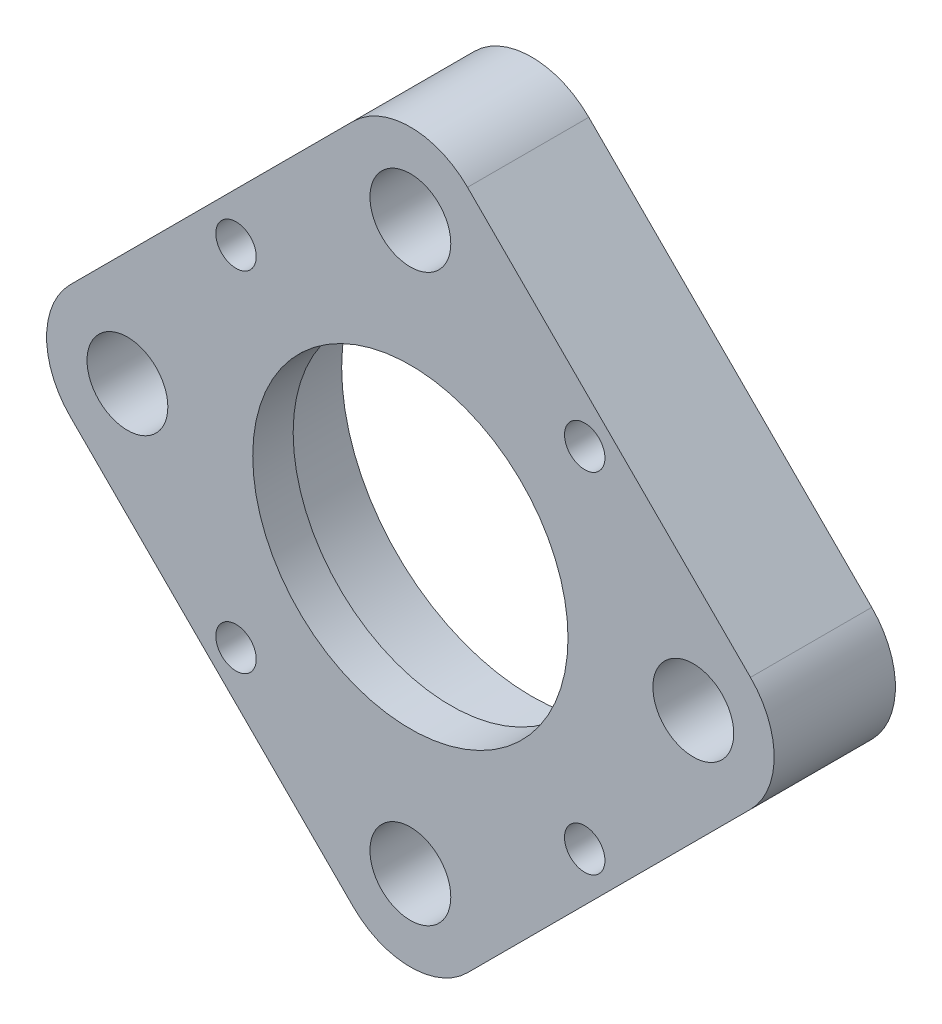
SolidWorks part; units mm, degrees
material "Stop 1060"
ref_plane "Płaszczyzna przednia" through (0, 0, 0) normal (0, 0, 1) x (1, 0, 0)
ref_plane "Płaszczyzna górna" through (0, 0, 0) normal (0, 1, 0) x (1, 0, 0)
ref_plane "Płaszczyzna prawa" through (0, 0, 0) normal (1, 0, 0) x (0, 0, -1)
sketch "Szkic1" plane through (0, 0, 0) normal (0, 0, 1) x (1, 0, 0)
  circle A0 centre (0, 0) radius 23.5
  circle A1 centre (0, 0) radius 19.5
  circle A2 centre (0, 0) radius 35
  dimension "D1" = 39
  dimension "D2" = 47
extrude "Dodanie-wyciągnięcie3" add sketch "Szkic1" along normal blind 5 contours A2 A0 | A0 A1
sketch "Szkic4" plane through (0, 0, 0) normal (0, 0, -1) x (-1, 0, 0)
  circle A0 centre (0, 0) radius 23.5
  circle A1 centre (0, 0) radius 35
  circle M2 centre (0, 0) radius 35
  dimension "D1" = 47
extrude "Dodanie-wyciągnięcie5" add sketch "Szkic4" along normal blind 10 contours A0 M2 | A1
sketch "Szkic10" plane through (0, 0, -10) normal (0, 0, -1) x (-1, 0, 0)
  circle A0 centre (0, 0) radius 30.5
  point P5 (-30.5, 0)
  point P6 (30.5, 0)
sketch "Szkic13" plane through (0, 0, -10) normal (0, 0, -1) x (-1, 0, 0)
  circle A0 centre (0, 35) radius 6
  circle A1 centre (0, 35) radius 10
  circle A3 centre (0, 0) radius 35
  circle A4 centre (0, -35) radius 6
  circle A5 centre (0, -35) radius 10
  circle A6 centre (-35, 0) radius 10
  circle A7 centre (35, 0) radius 10
  point P18 (-35, 0)
  point P20 (35, 0)
  dimension "D2" = 35
  dimension "D1" = 20
  dimension "D3" = 20
  dimension "D7" = 20
  dimension "D8" = 20
  dimension "D4" = 35
  dimension "D5" = 35
  dimension "D6" = 70
extrude "Dodanie-wyciągnięcie6" add sketch "Szkic13" against normal blind 15
sketch "Szkic16" plane through (0, 0, 5) normal (0, 0, 1) x (1, 0, 0)
  point P0 (0, -35)
  point P1 (0, 35)
  dimension "D1" = 70
hole_wizard "Otwory ustalające Ø10.0mm1" positions "Szkic17" profile "Szkic18" hole size "Ø10.0" standard "ISO" end condition through all
sketch "Szkic17" plane through (0, 0, 5) normal (0, 0, 1) x (1, 0, 0)
  point P0 (0, 35)
  point P3 (0, -35)
  point P7 (-35, 0)
  point P9 (35, 0)
  dimension "D1" = 35
  dimension "D2" = 70
sketch "Szkic18" plane through (0, 35, 5) normal (1, 0, 0) x (0, -1, 0)
  line L0 (0, 0) -> (0, 15)
  line L1 (0, 15) -> (5, 15)
  line L2 (5, 15) -> (5, 0)
  line L5 (5, 0) -> (0, 0)
  line L11 (0, -6.35) -> (0, 107.95) construction
  dimension "Średnica otworu na wylot" = 10
  dimension "Głębokość otworu na wylot" = 15
sketch "Szkic20" plane through (0, 0, 5) normal (0, 0, 1) x (1, 0, 0)
  line L0 (0, 0) -> (-21.5668, 21.5668)
  circle A0 centre (0, 0) radius 30.5
  point P4 (21.5668, 21.5668)
  point P5 (-21.5668, 21.5668)
  point P6 (21.5668, -21.5668)
  point P7 (-21.5668, -21.5668)
  dimension "D1" = 61
hole_wizard "Otwory ustalające Ø5.0mm3" positions "Szkic25" profile "Szkic26" hole size "Ø5.0" standard "ISO" end condition through all
sketch "Szkic25" plane through (0, 0, 5) normal (0, 0, 1) x (1, 0, 0)
  point P0 (-21.5668, 21.5668)
  point P3 (21.5668, 21.5668)
  point P6 (21.5668, -21.5668)
  point P9 (-21.5668, -21.5668)
sketch "Szkic26" plane through (-21.5668, 21.5668, 5) normal (1, 0, 0) x (0, -1, 0)
  line L0 (0, 0) -> (0, 15)
  line L1 (0, 15) -> (2.5, 15)
  line L2 (2.5, 15) -> (2.5, 0)
  line L5 (2.5, 0) -> (0, 0)
  line L11 (0, -6.35) -> (0, 107.95) construction
  dimension "Średnica otworu na wylot" = 5
  dimension "Głębokość otworu na wylot" = 15
fillet "Zaokrąglenie1" [suppressed] radius 360
sketch "Szkic27" plane through (0, 0, -10) normal (0, 0, -1) x (-1, 0, 0)
  line L0 (42.0711, -7.0711) -> (7.0711, -42.0711)
  line L1 (-7.0711, -42.0711) -> (-42.0711, -7.0711)
  line L2 (-42.0711, 7.0711) -> (-7.0711, 42.0711)
  line L3 (7.0711, 42.0711) -> (42.0711, 7.0711)
  line L4 (21.5668, 24.0668) -> (4.6384, 36.867)
  line L5 (-3.9414, 31.9234) -> (-19.4113, 22.8333)
  line L6 (-22.9036, 19.4542) -> (-32.481, 4.3191)
  line L7 (32.481, 4.3191) -> (22.9036, 19.4542)
  line L8 (32.481, -4.3191) -> (21.5668, -19.0668)
  line L9 (22.2032, -23.9844) -> (-1.2729, -30.1648)
  line L10 (-1.2729, -30.1648) -> (-19.2648, -22.542)
  line L11 (-32.481, -4.3191) -> (-22.9036, -19.4542)
  arc A0 (33.5714, -9.8974) -> (33.5714, 9.8974) centre (35, 0) ccw construction
  arc A1 (-9.8974, -33.5714) -> (9.8974, -33.5714) centre (0, -35) ccw construction
  arc A2 (-33.5714, 9.8974) -> (-33.5714, -9.8974) centre (-35, 0) ccw construction
  arc A3 (9.8974, 33.5714) -> (-9.8974, 33.5714) centre (0, 35) ccw construction
  arc A4 (42.0711, 7.0711) -> (42.0711, -7.0711) centre (35, 0) cw
  arc A5 (-7.0711, -42.0711) -> (7.0711, -42.0711) centre (0, -35) ccw
  arc A6 (-7.0711, 42.0711) -> (7.0711, 42.0711) centre (0, 35) cw
  arc A7 (-42.0711, -7.0711) -> (-42.0711, 7.0711) centre (-35, 0) cw
  circle A10 centre (35, 0) radius 5
  circle A11 centre (21.5668, 21.5668) radius 2.5
  circle A12 centre (21.5668, -21.5668) radius 2.5
  circle A13 centre (0, -35) radius 5
  circle A14 centre (-21.5668, -21.5668) radius 2.5
  circle A15 centre (-35, 0) radius 5
  circle A16 centre (-21.5668, 21.5668) radius 2.5
  circle A17 centre (0, 35) radius 5
  arc M19 (-9.8974, 33.5714) -> (-33.5714, 9.8974) centre (0, 0) ccw
  arc M20 (-33.5714, 9.8974) -> (-33.5714, -9.8974) centre (-35, 0) ccw
  arc M21 (-33.5714, -9.8974) -> (-9.8974, -33.5714) centre (0, 0) ccw
  arc M22 (-9.8974, -33.5714) -> (9.8974, -33.5714) centre (0, -35) ccw
  arc M23 (9.8974, -33.5714) -> (33.5714, -9.8974) centre (0, 0) ccw
  arc M24 (33.5714, -9.8974) -> (33.5714, 9.8974) centre (35, 0) ccw
  arc M25 (33.5714, 9.8974) -> (9.8974, 33.5714) centre (0, 0) ccw
  arc M26 (9.8974, 33.5714) -> (-9.8974, 33.5714) centre (0, 35) ccw
  dimension "D1" = 10
  dimension "D2" = 10
  dimension "D3" = 10
  dimension "D4" = 10
extrude "Dodanie-wyciągnięcie7" add sketch "Szkic27" against normal blind 15 contours L3 M25 M24 | L3 M26 M25 | L2 M19 M26 | L2 M20 M19 | L1 M21 M20 | L1 M22 M21 | L0 M23 M22 | L0 M24 M23
sketch "Szkic28" plane through (0, 0, -10) normal (0, 0, -1) x (-1, 0, 0)
  line L0 (42.0711, -7.0711) -> (0, -49.1421)
  line L1 (0, -49.1421) -> (-49.1421, 0)
  line L2 (-49.1421, 0) -> (0, 49.1421)
  line L3 (0, 49.1421) -> (49.1421, 0)
  line L4 (49.1421, 0) -> (41.0704, -8.0718)
  circle A0 centre (0, 0) radius 52.5094
  line M2 (42.0711, 7.0711) -> (27.5312, 21.6109)
  arc M3 (27.5312, 21.6109) -> (21.6109, 27.5312) centre (0, 0) ccw
  line M4 (21.6109, 27.5312) -> (7.0711, 42.0711)
  line M6 (-7.0711, 42.0711) -> (-21.6109, 27.5312)
  arc M7 (-21.6109, 27.5312) -> (-27.5312, 21.6109) centre (0, 0) ccw
  line M8 (-27.5312, 21.6109) -> (-42.0711, 7.0711)
  line M10 (-42.0711, -7.0711) -> (-27.5312, -21.6109)
  arc M11 (-27.5312, -21.6109) -> (-21.6109, -27.5312) centre (0, 0) ccw
  line M12 (-21.6109, -27.5312) -> (-7.0711, -42.0711)
  line M14 (7.0711, -42.0711) -> (21.6109, -27.5312)
  arc M15 (21.6109, -27.5312) -> (27.5312, -21.6109) centre (0, 0) ccw
  line M16 (27.5312, -21.6109) -> (42.0711, -7.0711)
extrude "Wytnij-wyciągnięcie6" cut sketch "Szkic28" against normal blind 15 contours A0 L3 L4 L0 L1 L2 M16 M15 M14 M12 M11 M10 M8 M7 M6 M4 M3 M2 | L0 M15 | L1 M11 | L2 M7 | L3 M3
